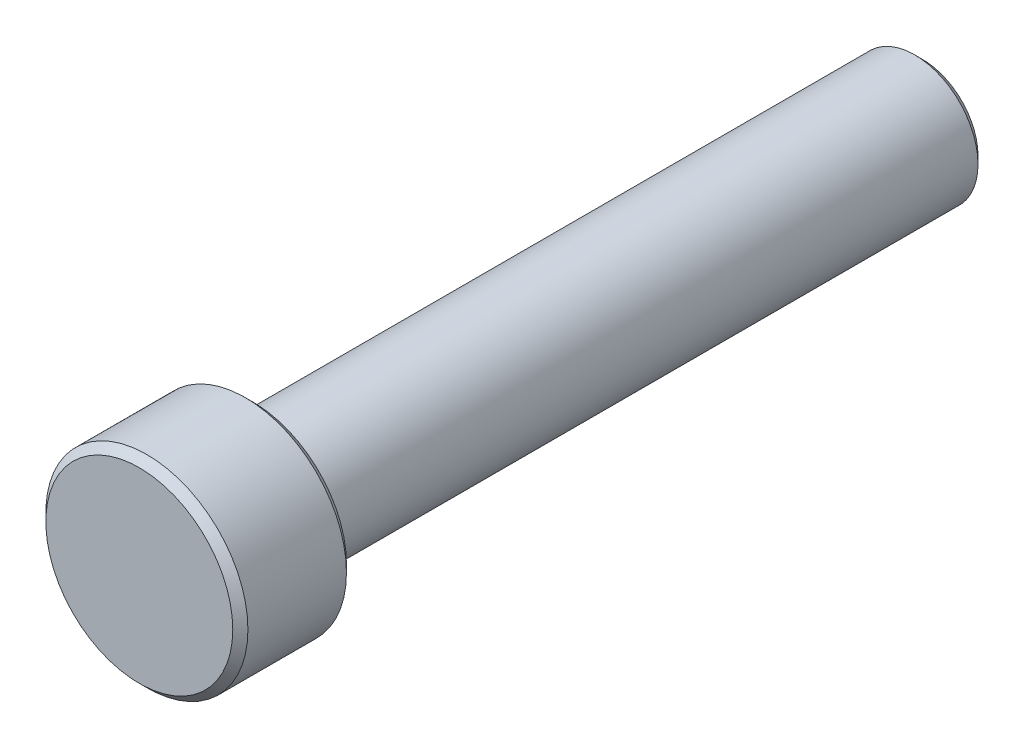
SolidWorks part; units mm, degrees
ref_plane "Front Plane" through (0, 0, 0) normal (0, 0, 1) x (1, 0, 0)
ref_plane "Top Plane" through (0, 0, 0) normal (0, 1, 0) x (1, 0, 0)
ref_plane "Right Plane" through (0, 0, 0) normal (1, 0, 0) x (0, 0, -1)
sketch "Sketch1" plane through (0, 0, 0) normal (0, 0, 1) x (1, 0, 0)
  circle A0 centre (0, 0) radius 2.5
  dimension "D1" = 5
extrude "Boss-Extrude1" add sketch "Sketch1" along normal blind 26.5
sketch "Sketch2" plane through (0, 0, 26.5) normal (0, 0, 1) x (1, 0, 0)
  circle A0 centre (0, 0) radius 4
  dimension "D1" = 8
extrude "Boss-Extrude2" add sketch "Sketch2" along normal blind 4.5
chamfer "Chamfer1" distance 0.3 angle 45 3 edges at (4, 0, 26.5) (4, 0, 31) (2.5, 0, 0)
